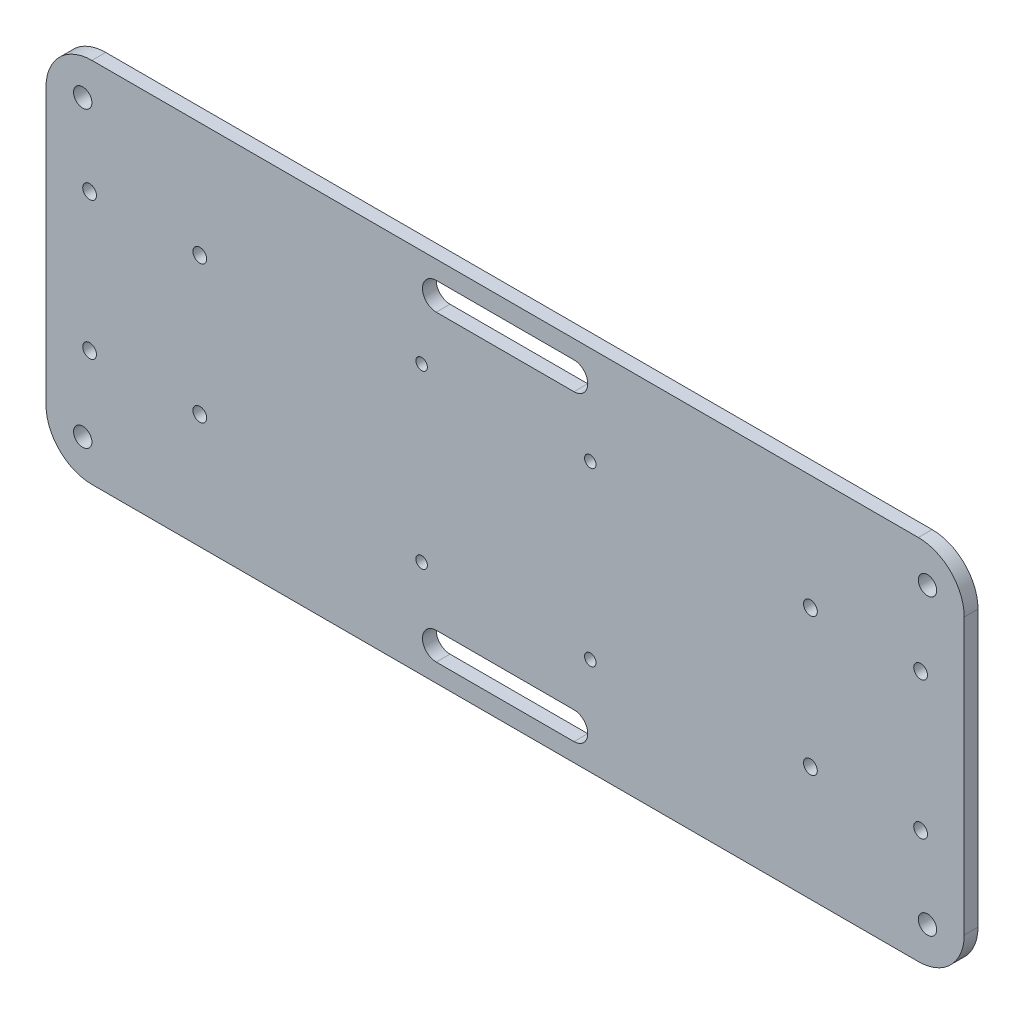
SolidWorks part; units mm, degrees
material "Mahogany"
ref_plane "Front Plane" through (0, 0, 0) normal (0, 0, 1) x (1, 0, 0)
ref_plane "Top Plane" through (0, 0, 0) normal (0, 1, 0) x (1, 0, 0)
ref_plane "Right Plane" through (0, 0, 0) normal (1, 0, 0) x (0, 0, -1)
sketch "Sketch1" plane through (0, 0, 0) normal (0, 0, 1) x (1, 0, 0)
  line L1 (-100, 40) -> (100, 40)
  line L2 (-100, 40) -> (-100, -40)
  line L3 (-100, -40) -> (100, -40)
  line L4 (100, 40) -> (100, -40)
  line L5 (-100, 40) -> (100, -40) construction
  line L6 (-100, -40) -> (100, 40) construction
  point P0 (0, 0)
  dimension "D1" = 80
  dimension "D2" = 200
extrude "Boss-Extrude1" add sketch "Sketch1" along normal blind 3
sketch "Sketch2" plane through (0, 0, 3) normal (0, 0, 1) x (1, 0, 0)
  line L0 (-100, 40) -> (-100, -40) construction
  line L1 (100, 40) -> (-100, 40) construction
  line L2 (0, 40) -> (0, -40) construction
  line L3 (-100, -40) -> (100, -40) construction
  line L4 (-100, 0) -> (100, 0) construction
  line L5 (100, -40) -> (100, 40) construction
  circle A0 centre (-92, 32) radius 2
  circle A1 centre (-92, -32) radius 2
  circle A2 centre (92, -32) radius 2
  circle A3 centre (92, 32) radius 2
  dimension "D1" = 4
  dimension "D2" = 8
  dimension "D3" = 8
extrude "Cut-Extrude1" cut sketch "Sketch2" against normal through all
fillet "Fillet1" radius 10 4 edges at (-100, -40, 1.5) (100, -40, 1.5) (100, 40, 1.5) (-100, 40, 1.5)
sketch "Sketch4" plane through (0, 0, 3) normal (0, 0, 1) x (1, 0, 0)
  line L0 (15, 33) -> (-15, 33) construction
  line L1 (15, 30) -> (-15, 30)
  line L2 (15, 36) -> (-15, 36)
  line L3 (90, 40) -> (-90, 40) construction
  line L4 (100, 0) -> (-100, 0) construction
  line L5 (100, -30) -> (100, 30) construction
  line L6 (-100, 30) -> (-100, -30) construction
  line L7 (15, -33) -> (-15, -33) construction
  line L8 (15, -30) -> (-15, -30)
  line L9 (15, -36) -> (-15, -36)
  arc A0 (15, 30) -> (15, 36) centre (15, 33) ccw
  arc A1 (-15, 36) -> (-15, 30) centre (-15, 33) ccw
  arc A2 (15, -30) -> (15, -36) centre (15, -33) cw
  arc A3 (-15, -36) -> (-15, -30) centre (-15, -33) cw
  point P2 (0, 33)
  point P9 (0, 40)
  point P18 (0, -33)
  dimension "D1" = 3
  dimension "D2" = 7
  dimension "D3" = 30
extrude "Cut-Extrude3" cut sketch "Sketch4" against normal through all
sketch "Sketch5" plane through (0, 0, 3) normal (0, 0, 1) x (1, 0, 0)
  circle A0 centre (18.5561, -18.7432) radius 1.25
  circle A1 centre (-18.1857, -18.7432) radius 1.25
  circle A2 centre (-18.1857, 18.6363) radius 1.25
  circle A3 centre (18.5561, 18.6363) radius 1.25
extrude "Cut-Extrude4" cut sketch "Sketch5" against normal through all
sketch "Sketch6" plane through (0, 0, 0) normal (0, 0, -1) x (-1, 0, 0)
  circle A0 centre (66.5, -15) radius 1.5
  circle A1 centre (90.5, -15) radius 1.5
  circle A2 centre (66.5, 15) radius 1.5
  circle A3 centre (90.5, 15) radius 1.5
  circle A4 centre (-90.5, -15) radius 1.5
  circle A5 centre (-66.5, -15) radius 1.5
  circle A6 centre (-66.5, 15) radius 1.5
  circle A7 centre (-90.5, 15) radius 1.5
extrude "Cut-Extrude5" cut sketch "Sketch6" against normal through all
